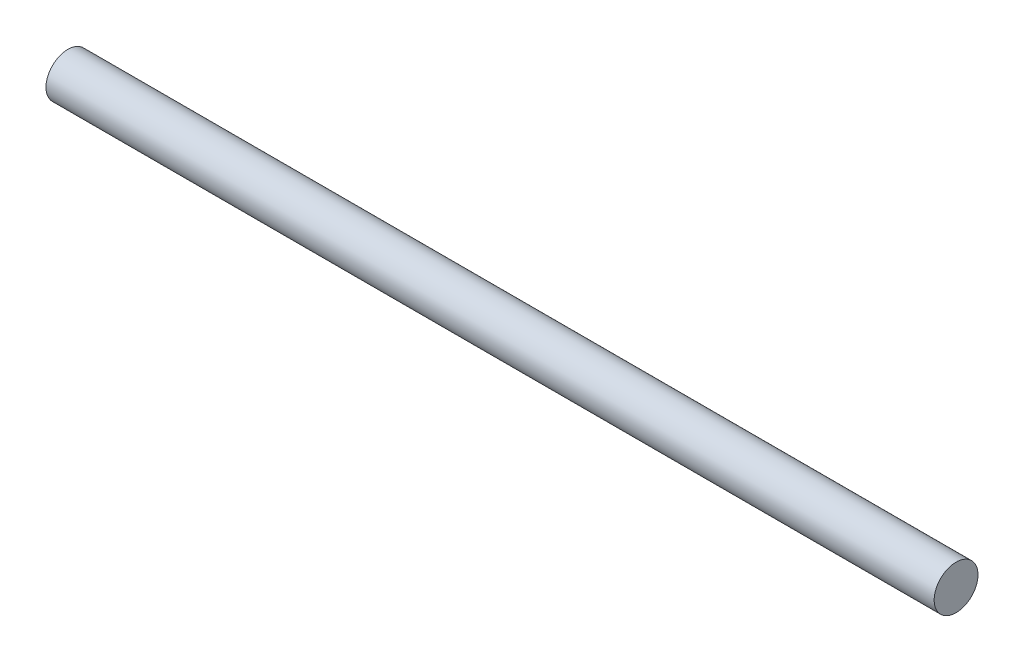
SolidWorks part; units mm, degrees
material "EN8"
ref_plane "Front Plane" through (0, 0, 0) normal (0, 0, 1) x (1, 0, 0)
ref_plane "Top Plane" through (0, 0, 0) normal (0, 1, 0) x (1, 0, 0)
ref_plane "Right Plane" through (0, 0, 0) normal (1, 0, 0) x (0, 0, -1)
sketch "Sketch2" plane through (0, 0, 0) normal (1, 0, 0) x (0, 0, -1)
  circle A0 centre (0, 0) radius 6
  dimension "D1" = 12
extrude "Boss-Extrude1" add sketch "Sketch2" against normal mid plane 243.0806
sketch "Sketch4" plane through (121.5403, 0, 0) normal (1, 0, 0) x (0, 0, -1)
  circle A5 centre (0, 0) radius 5
  dimension "D1" = 10
